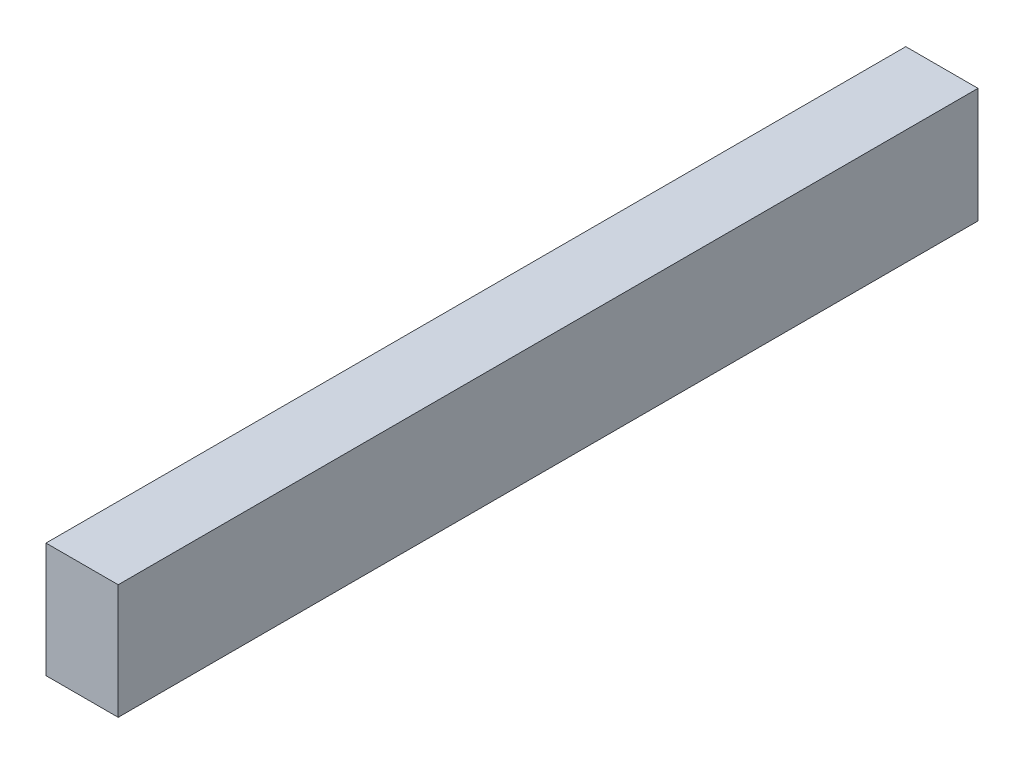
SolidWorks part; units mm, degrees
ref_plane "Front Plane" through (0, 0, 0) normal (0, 0, 1) x (1, 0, 0)
ref_plane "Top Plane" through (0, 0, 0) normal (0, 1, 0) x (1, 0, 0)
ref_plane "Right Plane" through (0, 0, 0) normal (1, 0, 0) x (0, 0, -1)
sketch "Sketch2" plane through (0, 0, 0) normal (0, 0, 1) x (1, 0, 0)
  line L1 (-29.5625, 10.5062) -> (-25.1625, 10.5062)
  line L2 (-29.5625, 10.5062) -> (-29.5625, 3.5062)
  line L3 (-29.5625, 3.5062) -> (-25.1625, 3.5062)
  line L4 (-25.1625, 10.5062) -> (-25.1625, 3.5062)
  dimension "D1" = 4.4
  dimension "D2" = 7
extrude "Boss-Extrude1" add sketch "Sketch2" along normal blind 52.4 contours L3 L4 L1 L2
